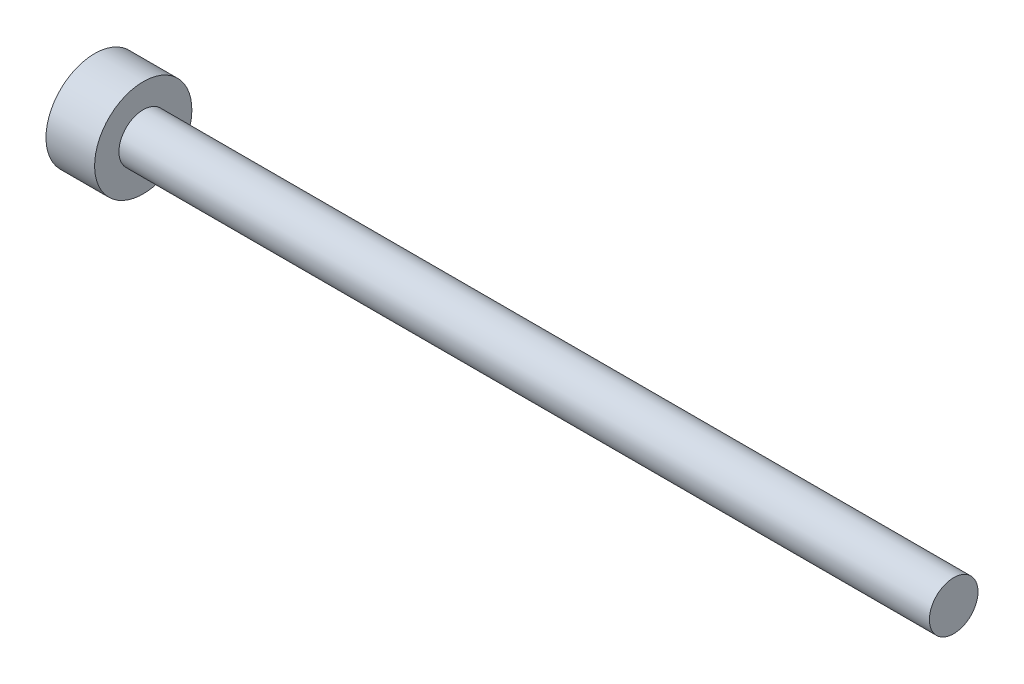
SolidWorks part; units mm, degrees
ref_plane "Front Plane" through (0, 0, 0) normal (0, 0, 1) x (1, 0, 0)
ref_plane "Top Plane" through (0, 0, 0) normal (0, 1, 0) x (1, 0, 0)
ref_plane "Right Plane" through (0, 0, 0) normal (1, 0, 0) x (0, 0, -1)
sketch "Sketch1" plane through (0, 0, 0) normal (0, 0, 1) x (1, 0, 0)
  line L1 (0, 0) -> (-50, 0)
  line L2 (0, 0) -> (0, 1.5)
  line L3 (0, 1.5) -> (-50, 1.5)
  line L4 (-50, 0) -> (-50, 1.5)
  line L5 (-50, 0) -> (-53, 0)
  line L6 (-50, 0) -> (-50, 3)
  line L7 (-50, 3) -> (-53, 3)
  line L8 (-53, 0) -> (-53, 3)
  dimension "D1" = 3
  dimension "D2" = 53
  dimension "D3" = 1.5
  dimension "D4" = 3
revolve "Revolve1" add sketch "Sketch1" angle 360 about L1
